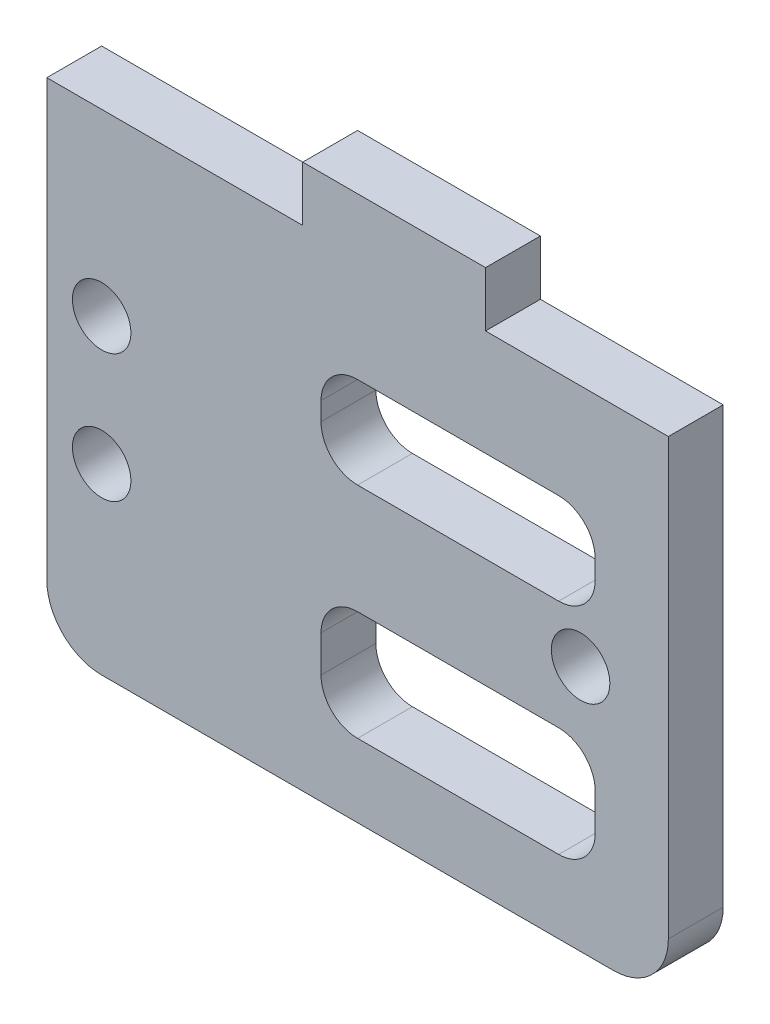
SolidWorks part; units mm, degrees
material "Thornel Mat VMA"
ref_plane "前视基准面" through (0, 0, 0) normal (0, 0, 1) x (1, 0, 0)
ref_plane "上视基准面" through (0, 0, 0) normal (0, 1, 0) x (1, 0, 0)
ref_plane "右视基准面" through (0, 0, 0) normal (1, 0, 0) x (0, 0, -1)
sketch "草图1" plane through (0, 0, 0) normal (0, 0, 1) x (1, 0, 0)
  line L0 (0, 0) -> (0, 26.8)
  line L1 (0, 26.8) -> (14, 26.8)
  line L2 (14, 26.8) -> (14, 29.8)
  line L3 (14, 29.8) -> (24, 29.8)
  line L4 (24, 29.8) -> (24, 26.8)
  line L5 (24, 26.8) -> (34, 26.8)
  line L6 (34, 26.8) -> (34, 0)
  line L7 (34, 0) -> (0, 0)
  line L8 (0, 13.5) -> (39.2681, 13.5) construction
  line L9 (15, 10) -> (30, 10)
  line L10 (15, 10) -> (15, 4)
  line L11 (15, 4) -> (30, 4)
  line L12 (30, 10) -> (30, 4)
  line L13 (15, 21) -> (30, 21)
  line L14 (15, 21) -> (15, 16)
  line L15 (15, 16) -> (30, 16)
  line L16 (30, 21) -> (30, 16)
  circle A0 centre (3, 17) radius 1.6
  circle A1 centre (3, 10) radius 1.6
  circle A3 centre (29.2, 13.5) radius 1.6
  dimension "D4" = 3.2
  dimension "D5" = 3
  dimension "D6" = 9.8
  dimension "D7" = 10
  dimension "D8" = 7
  dimension "D10" = 4
  dimension "D16" = 26.2
  dimension "D17" = 3.2
  dimension "D1" = 14
  dimension "D2" = 10
  dimension "D3" = 3
  dimension "D9" = 10
  dimension "D11" = 15
  dimension "D12" = 6
  dimension "D13" = 4
  dimension "D14" = 6
  dimension "D15" = 5
extrude "凸台-拉伸1" add sketch "草图1" along normal blind 3
fillet "圆角1" radius 2 8 edges at (15, 4, 1.5) (30, 4, 1.5) (30, 10, 1.5) (15, 10, 1.5) (30, 16, 1.5) (30, 21, 1.5) (15, 21, 1.5) (15, 16, 1.5)
fillet "圆角2" radius 3 2 edges at (34, 0, 1.5) (0, 0, 1.5)
